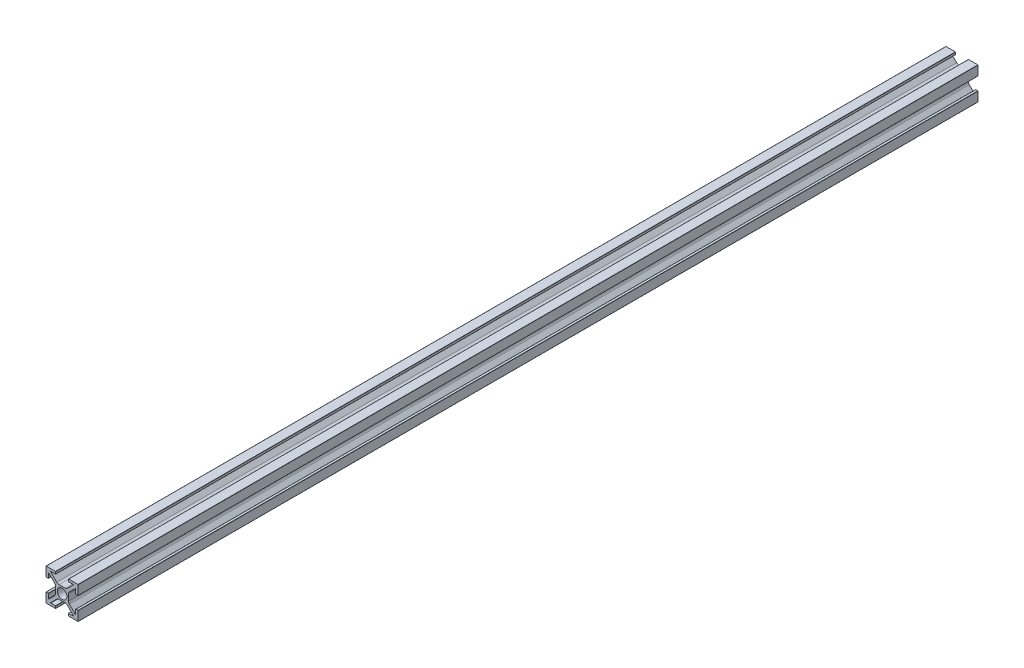
SolidWorks part; units mm, degrees
material "6061-T6 (SS)"
ref_plane "Front Plane" through (0, 0, 0) normal (0, 0, 1) x (1, 0, 0)
ref_plane "Top Plane" through (0, 0, 0) normal (0, 1, 0) x (1, 0, 0)
ref_plane "Right Plane" through (0, 0, 0) normal (1, 0, 0) x (0, 0, -1)
ref_plane "Plane1" through (0, 0, 60) normal (0, 0, 1) x (1, 0, 0)
sketch "Sketch1" plane through (0, 0, 60) normal (0, 0, 1) x (1, 0, 0)
  line L0 (18.5, 17.0086) -> (18.5, 14.1)
  line L1 (18.6, 14) -> (19.9, 14)
  line L2 (20, 14.1) -> (20, 19.9)
  line L3 (19.9, 20) -> (14.1, 20)
  line L4 (14, 19.9) -> (14, 18.6)
  line L5 (14.1, 18.5) -> (17.0086, 18.5)
  line L6 (17.0793, 18.3293) -> (13.3358, 14.5858)
  line L7 (11.9216, 14) -> (8.0784, 14)
  line L8 (6.6642, 14.5858) -> (2.9207, 18.3293)
  line L9 (2.9914, 18.5) -> (5.9, 18.5)
  line L10 (6, 18.6) -> (6, 19.9)
  line L11 (5.9, 20) -> (0.1, 20)
  line L12 (0, 19.9) -> (0, 14.1)
  line L13 (0.1, 14) -> (1.4, 14)
  line L14 (1.5, 14.1) -> (1.5, 17.0086)
  line L15 (1.6707, 17.0793) -> (5.4142, 13.3358)
  line L16 (6, 11.9216) -> (6, 8.0784)
  line L17 (5.4142, 6.6642) -> (1.6707, 2.9207)
  line L18 (1.5, 2.9914) -> (1.5, 5.9)
  line L19 (1.4, 6) -> (0.1, 6)
  line L20 (0, 5.9) -> (0, 0.1)
  line L21 (0.1, 0) -> (5.9, 0)
  line L22 (6, 0.1) -> (6, 1.4)
  line L23 (5.9, 1.5) -> (2.9914, 1.5)
  line L24 (2.9207, 1.6707) -> (6.6642, 5.4142)
  line L25 (8.0784, 6) -> (11.9216, 6)
  line L26 (13.3358, 5.4142) -> (17.0793, 1.6707)
  line L27 (17.0086, 1.5) -> (14.1, 1.5)
  line L28 (14, 1.4) -> (14, 0.1)
  line L29 (14.1, 0) -> (19.9, 0)
  line L30 (20, 0.1) -> (20, 5.9)
  line L31 (19.9, 6) -> (18.6, 6)
  line L32 (18.5, 5.9) -> (18.5, 2.9914)
  line L33 (18.3293, 2.9207) -> (14.5858, 6.6642)
  line L34 (14, 8.0784) -> (14, 11.9216)
  line L35 (14.5858, 13.3358) -> (18.3293, 17.0793)
  circle A0 centre (10, 10) radius 3
  arc A1 (18.3293, 17.0793) -> (18.5, 17.0086) centre (18.4, 17.0086) cw
  arc A2 (18.5, 14.1) -> (18.6, 14) centre (18.6, 14.1) ccw
  arc A3 (19.9, 14) -> (20, 14.1) centre (19.9, 14.1) ccw
  arc A4 (20, 19.9) -> (19.9, 20) centre (19.9, 19.9) ccw
  arc A5 (14.1, 20) -> (14, 19.9) centre (14.1, 19.9) ccw
  arc A6 (14, 18.6) -> (14.1, 18.5) centre (14.1, 18.6) ccw
  arc A7 (17.0086, 18.5) -> (17.0793, 18.3293) centre (17.0086, 18.4) cw
  arc A8 (13.3358, 14.5858) -> (11.9216, 14) centre (11.9216, 16) cw
  arc A9 (8.0784, 14) -> (6.6642, 14.5858) centre (8.0784, 16) cw
  arc A10 (2.9207, 18.3293) -> (2.9914, 18.5) centre (2.9914, 18.4) cw
  arc A11 (5.9, 18.5) -> (6, 18.6) centre (5.9, 18.6) ccw
  arc A12 (6, 19.9) -> (5.9, 20) centre (5.9, 19.9) ccw
  arc A13 (0.1, 20) -> (0, 19.9) centre (0.1, 19.9) ccw
  arc A14 (0, 14.1) -> (0.1, 14) centre (0.1, 14.1) ccw
  arc A15 (1.4, 14) -> (1.5, 14.1) centre (1.4, 14.1) ccw
  arc A16 (1.5, 17.0086) -> (1.6707, 17.0793) centre (1.6, 17.0086) cw
  arc A17 (5.4142, 13.3358) -> (6, 11.9216) centre (4, 11.9216) cw
  arc A18 (6, 8.0784) -> (5.4142, 6.6642) centre (4, 8.0784) cw
  arc A19 (1.6707, 2.9207) -> (1.5, 2.9914) centre (1.6, 2.9914) cw
  arc A20 (1.5, 5.9) -> (1.4, 6) centre (1.4, 5.9) ccw
  arc A21 (0.1, 6) -> (0, 5.9) centre (0.1, 5.9) ccw
  arc A22 (0, 0.1) -> (0.1, 0) centre (0.1, 0.1) ccw
  arc A23 (5.9, 0) -> (6, 0.1) centre (5.9, 0.1) ccw
  arc A24 (6, 1.4) -> (5.9, 1.5) centre (5.9, 1.4) ccw
  arc A25 (2.9914, 1.5) -> (2.9207, 1.6707) centre (2.9914, 1.6) cw
  arc A26 (6.6642, 5.4142) -> (8.0784, 6) centre (8.0784, 4) cw
  arc A27 (11.9216, 6) -> (13.3358, 5.4142) centre (11.9216, 4) cw
  arc A28 (17.0793, 1.6707) -> (17.0086, 1.5) centre (17.0086, 1.6) cw
  arc A29 (14.1, 1.5) -> (14, 1.4) centre (14.1, 1.4) ccw
  arc A30 (14, 0.1) -> (14.1, 0) centre (14.1, 0.1) ccw
  arc A31 (19.9, 0) -> (20, 0.1) centre (19.9, 0.1) ccw
  arc A32 (20, 5.9) -> (19.9, 6) centre (19.9, 5.9) ccw
  arc A33 (18.6, 6) -> (18.5, 5.9) centre (18.6, 5.9) ccw
  arc A34 (18.5, 2.9914) -> (18.3293, 2.9207) centre (18.4, 2.9914) cw
  arc A35 (14.5858, 6.6642) -> (14, 8.0784) centre (16, 8.0784) cw
  arc A36 (14, 11.9216) -> (14.5858, 13.3358) centre (16, 11.9216) cw
extrude "Boss-Extrude2" add sketch "Sketch1" along normal blind 560
